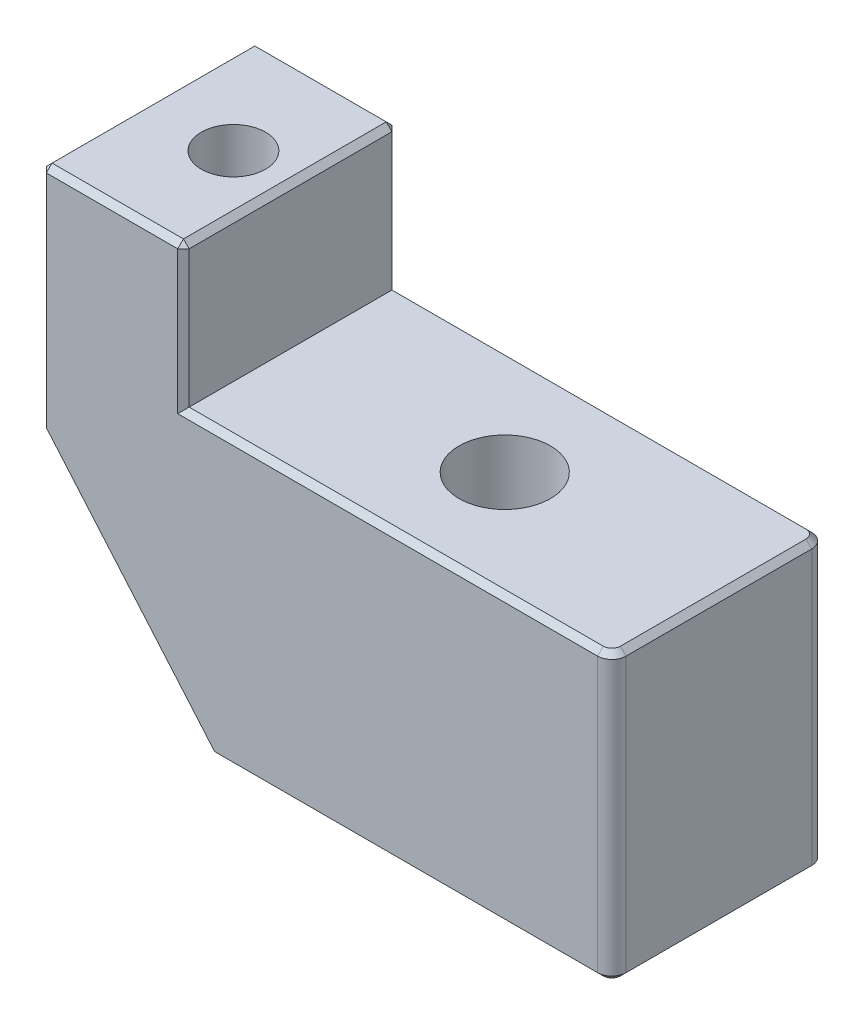
SolidWorks part; units mm, degrees
material "ABS"
ref_plane "Front Plane" through (0, 0, 0) normal (0, 0, 1) x (1, 0, 0)
ref_plane "Top Plane" through (0, 0, 0) normal (0, 1, 0) x (1, 0, 0)
ref_plane "Right Plane" through (0, 0, 0) normal (1, 0, 0) x (0, 0, -1)
sketch "Sketch1" plane through (0, 0, 0) normal (0, 0, 1) x (1, 0, 0)
  line L0 (0, 0) -> (0, 16)
  line L3 (0, 16) -> (10, 16)
  line L4 (10, 16) -> (10, 6)
  line L5 (10, 6) -> (40, 6)
  line L6 (40, 6) -> (40, 0)
  line L7 (40, 0) -> (0, 0) construction
  line L9 (0, 0) -> (12, -14)
  line L10 (12, -14) -> (40, -14)
  line L11 (40, -14) -> (40, 0)
  point P4 (0, 0)
  point P10 (12, -5.4723)
  dimension "D1" = 10
  dimension "D2" = 12
  dimension "D3" = 20
  dimension "D4" = 10
  dimension "D5" = 30
  dimension "D6" = 16
extrude "Boss-Extrude1" add sketch "Sketch1" along normal mid plane 15
hole_wizard "CBORE for M6 Hex Socket Head Cap Screw1" positions "Sketch2" profile "Sketch3" counterbore size "M6" standard "DIN" end condition up to next
sketch "Sketch2" plane through (0, -14, 0) normal (0, -1, 0) x (-1, 0, 0)
  line L1 (0, 0) -> (-25, 0) construction
  line L3 (-40, -7.5) -> (-40, 7.5) construction
  point P0 (-25, 0)
  point P12 (0, 0)
  point P13 (-2.7673, 0)
  dimension "D1" = 15
sketch "Sketch3" plane through (25, -14, 0) normal (1, 0, 0) x (0, 0, -1)
  line L0 (0, 0) -> (0, 20)
  line L1 (0, 20) -> (3.2, 20)
  line L3 (3.2, 20) -> (3.2, 6.4)
  line L4 (3.2, 6.4) -> (5.5, 6.4)
  line L5 (5.5, 6.4) -> (5.5, 0)
  line L7 (5.5, 0) -> (0, 0)
  line L11 (0, -6.35) -> (0, 107.95) construction
  dimension "Thru Hole Dia." = 6.4
  dimension "Thru Hole Depth" = 20
  dimension "C'Bore Dia." = 11
  dimension "C'Bore Depth" = 6.4
hole_wizard "Tap Drill for M4 Tap1" positions "Sketch4" profile "Sketch5" hole size "M4" standard "DIN" end condition up to next
sketch "Sketch4" plane through (16, 16, 0) normal (0, -1, 0) x (0, 0, 1)
  line L0 (0, 16) -> (0, 10) construction
  line L3 (7.5, 6) -> (-7.5, 6) construction
  point P0 (0, 10)
  point P9 (0, 12.1074)
  dimension "D1" = 4
sketch "Sketch5" plane through (6, 16, 0) normal (1, 0, 0) x (0, 0, 1)
  line L0 (0, 0) -> (0, 23)
  line L1 (0, 23) -> (1.65, 23)
  line L2 (1.65, 23) -> (1.65, 0)
  line L5 (1.65, 0) -> (0, 0)
  line L11 (0, -6.35) -> (0, 107.95) construction
  dimension "Thru Hole Dia." = 3.3
  dimension "Thru Hole Depth" = 23
hole_wizard "CBORE for M4 Hex Socket Head Cap Screw1" positions "Sketch6" profile "Sketch8" counterbore size "M4" standard "DIN" end condition up to next
sketch "Sketch6" plane through (0, -14, 0) normal (0, -1, 0) x (-1, 0, 0)
  point P0 (-6, 0)
sketch "Sketch8" plane through (6, -14, 0) normal (1, 0, 0) x (0, 0, -1)
  line L0 (0, 0) -> (0, 30)
  line L1 (0, 30) -> (2.25, 30)
  line L3 (2.25, 30) -> (2.25, 16.4)
  line L4 (2.25, 16.4) -> (4, 16.4)
  line L5 (4, 16.4) -> (4, 0)
  line L7 (4, 0) -> (0, 0)
  line L11 (0, -6.35) -> (0, 107.95) construction
  dimension "Thru Hole Dia." = 4.5
  dimension "Thru Hole Depth" = 30
  dimension "C'Bore Dia." = 8
  dimension "C'Bore Depth" = 16.4
fillet "Fillet1" radius 1 2 edges at (40, -4, -7.5) (40, -4, 7.5)
chamfer "Chamfer1" distance 0.4 angle 45 20 edges at (10, 16, 0) (5, 16, -7.5) (5, 16, 7.5) (40, 6, 0) (24.5, 6, -7.5) (24.5, 6, 7.5) (10, 11, -7.5) (10, 11, 7.5) (39.7071, 6, -7.2071) (39.7071, 6, 7.2071) (25.5, -14, 7.5) (39.7071, -14, 7.2071) (40, -14, 0) (39.7071, -14, -7.2071) (25.5, -14, -7.5) (6, -7, 7.5) (0, 8, 7.5) (6, -7, -7.5) (0, 8, -7.5) (0, 16, 0)
